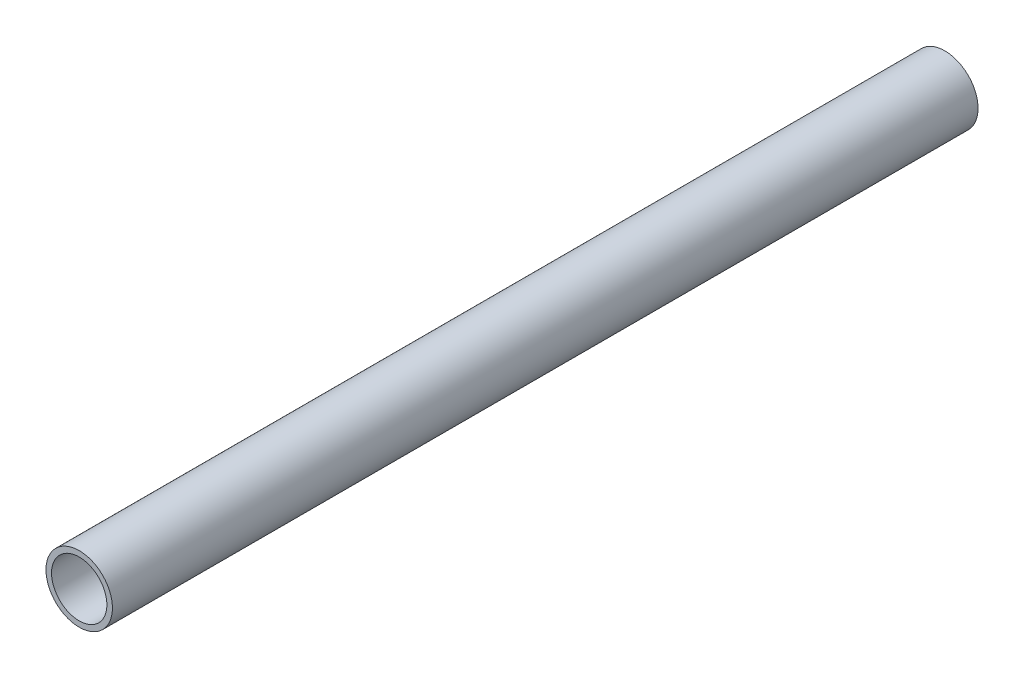
SolidWorks part; units mm, degrees
ref_plane "Front Plane" through (0, 0, 0) normal (0, 0, 1) x (1, 0, 0)
ref_plane "Top Plane" through (0, 0, 0) normal (0, 1, 0) x (1, 0, 0)
ref_plane "Right Plane" through (0, 0, 0) normal (1, 0, 0) x (0, 0, -1)
sketch "Sketch1" plane through (0, 0, 0) normal (0, 0, 1) x (1, 0, 0)
  circle A0 centre (0, 0) radius 15
  circle A1 centre (0, 0) radius 12.5
  dimension "D1" = 30
  dimension "D2" = 25
extrude "Boss-Extrude1" add sketch "Sketch1" along normal blind 391
